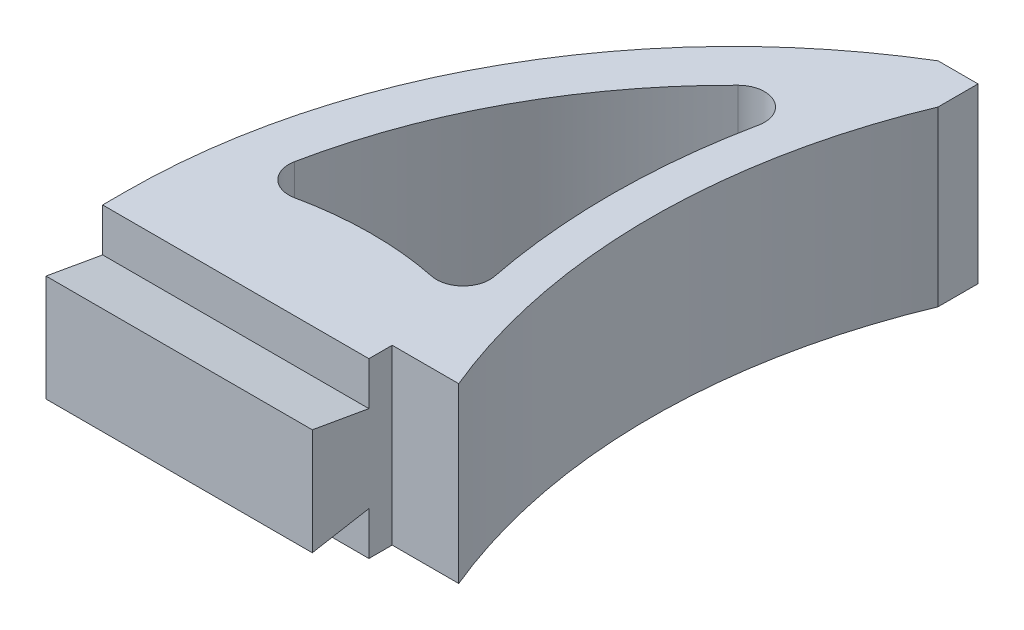
SolidWorks part; units mm, degrees
ref_plane "前视基准面" through (0, 0, 0) normal (0, 0, 1) x (1, 0, 0)
ref_plane "上视基准面" through (0, 0, 0) normal (0, 1, 0) x (1, 0, 0)
ref_plane "右视基准面" through (0, 0, 0) normal (1, 0, 0) x (0, 0, -1)
other "Configuration Table"
sketch "草图1" plane through (0, 0, 0) normal (0, 1, 0) x (1, 0, 0)
  line L0 (25, 39) -> (22, 39)
  line L2 (0, 0) -> (0, -6)
  line L3 (0, -6) -> (20, -6)
  line L4 (20, 0) -> (20, -6)
  line L5 (25, 39) -> (25, 36)
  line L6 (20, 0) -> (25, 0)
  line L7 (21.4141, 35.0518) -> (21.4141, 35.0518)
  line L8 (21.4141, 35.0518) -> (21.4141, 35.0518)
  line L13 (17, 3) -> (17, -3) construction
  line L14 (17, 3) -> (20.7196, 3) construction
  line L15 (3, -3) -> (17, -3) construction
  line L16 (3, 0) -> (3, -3) construction
  arc A1 (0, 0) -> (22, 39) centre (45.5682, 0) cw
  arc A2 (25, 0) -> (25, 36) centre (68.4166, 18) cw
  arc A3 (19.3624, 8.3209) -> (19.4432, 28.08) centre (68.4166, 18) cw
  arc A5 (3, 0) -> (21.4141, 35.0518) centre (45.5682, 0) cw construction
  arc A6 (16.0801, 29.9074) -> (4.3924, 8.2798) centre (45.5682, 0) ccw
  arc A7 (20.7196, 3) -> (21.4141, 35.0518) centre (68.4166, 18) cw construction
  arc A8 (6.7708, 5.9296) -> (16.9996, 5.9743) centre (11.9921, -18.5191) cw
  arc A9 (4.3924, 8.2798) -> (6.7708, 5.9296) centre (6.3532, 7.8855) ccw
  arc A10 (16.9996, 5.9743) -> (19.3624, 8.3209) centre (17.4002, 7.9337) ccw
  arc A11 (16.0801, 29.9074) -> (19.4432, 28.08) centre (17.4843, 28.4832) cw
  point P6 (25, 39)
  point P24 (20.1016, 5.1291)
  point P25 (3.8825, 5.1291)
  point P30 (3.8825, 5.1291)
  point P33 (20.1016, 5.1291)
  point P36 (21.0895, 34.1291)
  dimension "D1" = 20
  dimension "D7" = 45.5682
  dimension "D8" = 47
  dimension "D10" = 84
  dimension "D12" = 25
  dimension "D13" = 2
  dimension "D2" = 6
  dimension "D3" = 25
  dimension "D4" = 3
  dimension "D5" = 3
  dimension "D6" = 3
  dimension "D9" = 5
  dimension "D11" = 29
extrude "凸台-拉伸1" add sketch "草图1" along normal blind 13 contours L6 A2 L5 L0 A1 L2 L3 L4 A6 A11 A3 A10 A8 A9
sketch "草图2" plane through (0, 0, 0) normal (-1, 0, 0) x (0, 0, 1)
  line L0 (1.7465, 13) -> (1.7465, 9.75)
  line L1 (0, 13) -> (-39, 13) construction
  line L2 (1.7465, 9.75) -> (6, 10.5)
  line L3 (6, 13) -> (6, 0) construction
  line L4 (6, 10.5) -> (6, 13)
  line L5 (0, 13) -> (6, 13) construction
  line L6 (6, 13) -> (1.7465, 13)
  line L7 (6, 6.5) -> (-39, 6.5) construction
  line L8 (-39, 13) -> (-39, 0) construction
  line L9 (6, 2.5) -> (6, 0)
  line L10 (1.7465, 3.25) -> (6, 2.5)
  line L11 (1.7465, 0) -> (1.7465, 3.25)
  line L12 (6, 0) -> (1.7465, 0)
  point P18 (-4.2011, 4.6104)
  point P19 (-4.2011, 4.6104)
  point P20 (0.8971, 9.75)
  dimension "D1" = 6.5
  dimension "D2" = 8
  dimension "D3" = 80
extrude "切除-拉伸1" cut sketch "草图2" against normal through all
